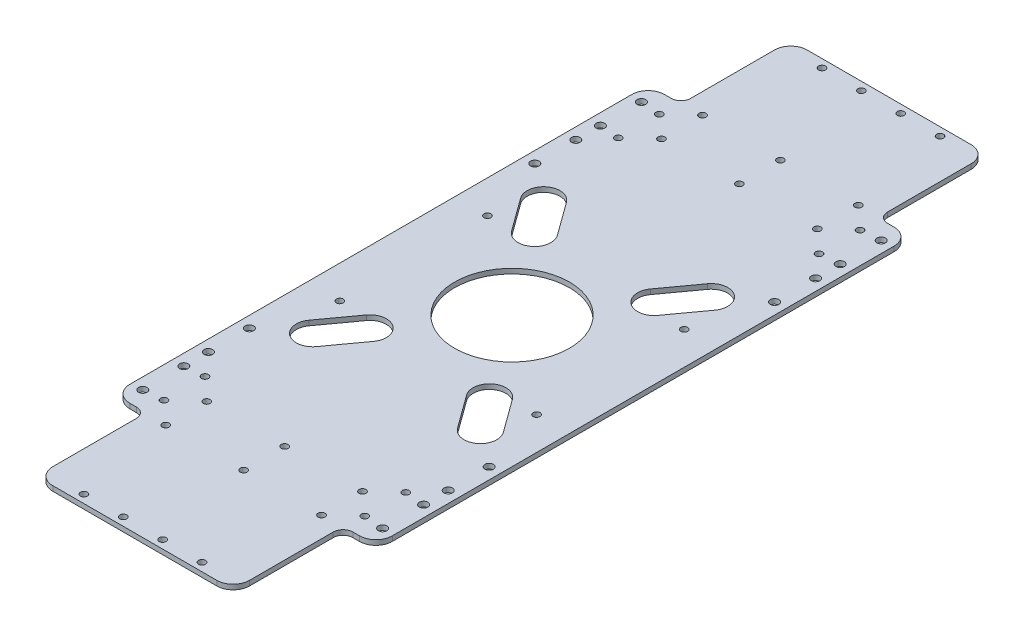
SolidWorks part; units mm, degrees
ref_plane "前视基准面" through (0, 0, 0) normal (0, 0, 1) x (1, 0, 0)
ref_plane "上视基准面" through (0, 0, 0) normal (0, 1, 0) x (1, 0, 0)
ref_plane "右视基准面" through (0, 0, 0) normal (1, 0, 0) x (0, 0, -1)
sketch "草图1" plane through (0, 0, 0) normal (0, 1, 0) x (1, 0, 0)
  line L7 (-299.537, 55) -> (462.4904, 55) construction
  line L8 (165, -108) -> (161, -108)
  line L10 (175, -25) -> (175, -98)
  line L31 (95, 38.3233) -> (95, -11.2332) construction
  line L58 (155, -114) -> (155, -165)
  line L65 (175, 135) -> (175, -25)
  line L66 (15, 135) -> (15, -25)
  line L67 (35, -114) -> (35, -165)
  line L68 (15, -25) -> (15, -98)
  line L69 (25, -108) -> (29, -108)
  line L70 (145, -175) -> (45, -175)
  line L72 (145, 285) -> (45, 285)
  line L73 (25, 218) -> (29, 218)
  line L74 (15, 135) -> (15, 208)
  line L75 (35, 224) -> (35, 275)
  line L76 (155, 224) -> (155, 275)
  line L77 (175, 135) -> (175, 208)
  line L78 (165, 218) -> (161, 218)
  arc A11 (165, -108) -> (175, -98) centre (165, -98) ccw
  arc A13 (155, -114) -> (161, -108) centre (161, -114) cw
  arc A37 (145, -175) -> (155, -165) centre (145, -165) ccw
  arc A40 (45, -175) -> (35, -165) centre (45, -165) cw
  arc A41 (35, -114) -> (29, -108) centre (29, -114) ccw
  arc A42 (25, -108) -> (15, -98) centre (25, -98) cw
  arc A43 (25, 218) -> (15, 208) centre (25, 208) ccw
  arc A44 (35, 224) -> (29, 218) centre (29, 224) cw
  arc A45 (45, 285) -> (35, 275) centre (45, 275) ccw
  arc A46 (145, 285) -> (155, 275) centre (145, 275) cw
  arc A47 (155, 224) -> (161, 218) centre (161, 224) ccw
  arc A48 (165, 218) -> (175, 208) centre (165, 208) cw
  point P0 (175, 55)
  point P1 (155, 285)
  point P18 (35, -175)
  point P19 (35, -174.6)
  point P38 (155, -174.6)
  point P48 (15, 55)
  point P49 (175, 55)
  point P51 (155, 284.6)
  point P52 (35, 284.6)
  point P53 (35, 285)
  point P66 (155, -175)
  dimension "D7" = 163
  dimension "D2" = 6
  dimension "D3" = 10
  dimension "D1" = 10
  dimension "D4" = 4
  dimension "D5" = 67
  dimension "D6" = 100
extrude "凸台-拉伸1" add sketch "草图1" along normal blind 3
sketch "草图2" plane through (0, 0, 0) normal (0, -1, 0) x (1, 0, 0)
  line L0 (45, 175) -> (145, 175) construction
  line L1 (175, 98) -> (175, -208) construction
  line L2 (95, -55) -> (164.7872, -55) construction
  line L3 (95, -55) -> (95, -139.4366) construction
  line L4 (175, 32) -> (175, 0) construction
  line L5 (175, 98) -> (175, -208) construction
  line L6 (175, 32) -> (175, 57) construction
  line L7 (175, 57) -> (175, 72) construction
  line L8 (175, 72) -> (175, 97) construction
  line L9 (175, 32) -> (168.1, 32) construction
  line L10 (168.1, 32) -> (168.1, 57) construction
  line L11 (168.1, 57) -> (168.1, 72) construction
  line L12 (168.1, 72) -> (168.1, 97) construction
  line L13 (142.5, 108.6322) -> (142.5, 83.6322) construction
  line L14 (35, 114) -> (35, 165) construction
  line L15 (21.9, 72) -> (21.9, 97) construction
  line L16 (21.9, 57) -> (21.9, 72) construction
  line L17 (142.5, -218.6322) -> (142.5, -193.6322) construction
  line L18 (21.9, 32) -> (21.9, 57) construction
  line L19 (21.9, -142) -> (21.9, -167) construction
  line L20 (21.9, -167) -> (21.9, -182) construction
  line L21 (21.9, -182) -> (21.9, -207) construction
  line L22 (168.1, -182) -> (168.1, -207) construction
  line L23 (168.1, -167) -> (168.1, -182) construction
  line L24 (168.1, -142) -> (168.1, -167) construction
  line L25 (175, -142) -> (168.1, -142) construction
  line L26 (175, -182) -> (175, -207) construction
  line L27 (175, -167) -> (175, -182) construction
  line L28 (175, -142) -> (175, -167) construction
  line L29 (175, -142) -> (175, -110) construction
  line L30 (145, -285) -> (45, -285) construction
  line L31 (131, -280) -> (107, -280) construction
  line L32 (107, -280) -> (83, -280) construction
  line L33 (83, -280) -> (59, -280) construction
  circle A6 centre (168.1, 97) radius 2.6
  circle A7 centre (168.1, 72) radius 2.6
  circle A8 centre (168.1, 57) radius 2.6
  circle A9 centre (168.1, 32) radius 2.6
  circle A34 centre (95, -55) radius 35
  circle A47 centre (59, 170) radius 2.1
  circle A75 centre (83, 170) radius 2.1
  circle A76 centre (107, 170) radius 2.1
  circle A77 centre (131, 170) radius 2.1
  circle A78 centre (131, -280) radius 2.1
  circle A79 centre (107, -280) radius 2.1
  circle A80 centre (83, -280) radius 2.1
  circle A81 centre (59, -280) radius 2.1
  circle A82 centre (142.5, 108.6322) radius 2.1
  circle A83 centre (142.5, 83.6322) radius 2.1
  circle A84 centre (95, 83.6322) radius 2.1
  circle A85 centre (95, 108.6322) radius 2.1
  circle A86 centre (47.5, 83.6322) radius 2.1
  circle A87 centre (47.5, 108.6322) radius 2.1
  circle A88 centre (47.5, -218.6322) radius 2.1
  circle A89 centre (47.5, -193.6322) radius 2.1
  circle A90 centre (95, -218.6322) radius 2.1
  circle A91 centre (95, -193.6322) radius 2.1
  circle A92 centre (142.5, -193.6322) radius 2.1
  circle A93 centre (142.5, -218.6322) radius 2.1
  circle A106 centre (21.9, 32) radius 2.6
  circle A107 centre (21.9, 57) radius 2.6
  circle A108 centre (21.9, 72) radius 2.6
  circle A109 centre (21.9, 97) radius 2.6
  circle A110 centre (21.9, -207) radius 2.6
  circle A111 centre (21.9, -182) radius 2.6
  circle A112 centre (21.9, -167) radius 2.6
  circle A113 centre (21.9, -142) radius 2.6
  circle A114 centre (168.1, -142) radius 2.6
  circle A115 centre (168.1, -167) radius 2.6
  circle A116 centre (168.1, -182) radius 2.6
  circle A117 centre (168.1, -207) radius 2.6
  point P10 (175, 0)
  point P52 (175, -55)
  dimension "D4" = 4.2
  dimension "D5" = 5
  dimension "D12" = 4.2
  dimension "D13" = 5
  dimension "D14" = 5.2
  dimension "D20" = 4.2
  dimension "D6" = 24
  dimension "D24" = 70
  dimension "D3" = 25
  dimension "D7" = 87
  dimension "D8" = 25
  dimension "D9" = 15
  dimension "D10" = 25
  dimension "D11" = 6.9
  dimension "D18" = 4
extrude "切除-拉伸1" cut sketch "草图2" against normal blind 10
sketch "草图3" plane through (0, 0, 0) normal (0, -1, 0) x (1, 0, 0)
  line L0 (95, -55) -> (95, -117) construction
  line L3 (35.7725, -119.5066) -> (50.4671, -99.2812)
  line L4 (51.9529, -131.2623) -> (66.6475, -111.0369)
  line L9 (51.9529, 21.2623) -> (66.6475, 1.0369)
  line L10 (35.7725, 9.5066) -> (50.4671, -10.7188)
  line L15 (154.2275, 9.5066) -> (139.5329, -10.7188)
  line L16 (138.0471, 21.2623) -> (123.3525, 1.0369)
  line L17 (95, -55) -> (18.3529, -55) construction
  line L22 (138.0471, -131.2623) -> (123.3525, -111.0369)
  line L23 (154.2275, -119.5066) -> (139.5329, -99.2812)
  arc A10 (66.6475, 1.0369) -> (50.4671, -10.7188) centre (58.5573, -4.8409) cw
  arc A11 (51.9529, 21.2623) -> (35.7725, 9.5066) centre (43.8627, 15.3845) ccw
  arc A16 (51.9529, -131.2623) -> (35.7725, -119.5066) centre (43.8627, -125.3845) cw
  arc A17 (66.6475, -111.0369) -> (50.4671, -99.2812) centre (58.5573, -105.1591) ccw
  arc A18 (123.3525, -111.0369) -> (139.5329, -99.2812) centre (131.4427, -105.1591) cw
  arc A19 (138.0471, -131.2623) -> (154.2275, -119.5066) centre (146.1373, -125.3845) ccw
  arc A20 (138.0471, 21.2623) -> (154.2275, 9.5066) centre (146.1373, 15.3845) cw
  arc A21 (123.3525, 1.0369) -> (139.5329, -10.7188) centre (131.4427, -4.8409) ccw
  point P5 (66.6475, 1.0369)
  point P6 (50.4671, -10.7188)
  point P38 (95, -55)
  dimension "D2" = 25
  dimension "D3" = 25
extrude "切除-拉伸2" cut sketch "草图3" against normal blind 10
sketch "草图8" plane through (0, 3, 0) normal (0, 1, 0) x (1, 0, 0)
  line L0 (95, 55) -> (95, 29.0654) construction
  line L2 (95, 55) -> (155, 55) construction
  line L3 (155, 55) -> (155, 10) construction
  circle A4 centre (155, 10) radius 2.1
  circle A5 centre (155, 100) radius 2.1
  circle A6 centre (35, 10) radius 2.1
  circle A7 centre (35, 100) radius 2.1
  dimension "D1" = 4.2
  dimension "D4" = 60
  dimension "D5" = 45
extrude "切除-拉伸6" cut sketch "草图8" against normal blind 10
sketch "草图9" plane through (0, 3, 0) normal (0, 1, 0) x (1, 0, 0)
  line L0 (95, 55) -> (95, -12.463) construction
  line L1 (95, 55) -> (155.2751, 55) construction
  line L2 (156.2, -71) -> (156.2, -96) construction
  line L3 (175, -98) -> (175, 208) construction
  line L4 (161, -108) -> (165, -108) construction
  circle A0 centre (156.2, -71) radius 2.1
  circle A1 centre (156.2, -96) radius 2.1
  circle A2 centre (33.8, -96) radius 2.1
  circle A3 centre (33.8, -71) radius 2.1
  circle A4 centre (156.2, 181) radius 2.1
  circle A5 centre (156.2, 206) radius 2.1
  circle A6 centre (33.8, 181) radius 2.1
  circle A7 centre (33.8, 206) radius 2.1
  dimension "D3" = 4.2
  dimension "D4" = 4.2
  dimension "D2" = 12
  dimension "D5" = 25
  dimension "D1" = 18.8
extrude "切除-拉伸7" cut sketch "草图9" against normal blind 10
equation "\"24。8\"=24"
equation "\"12。5\"=24.3239"
